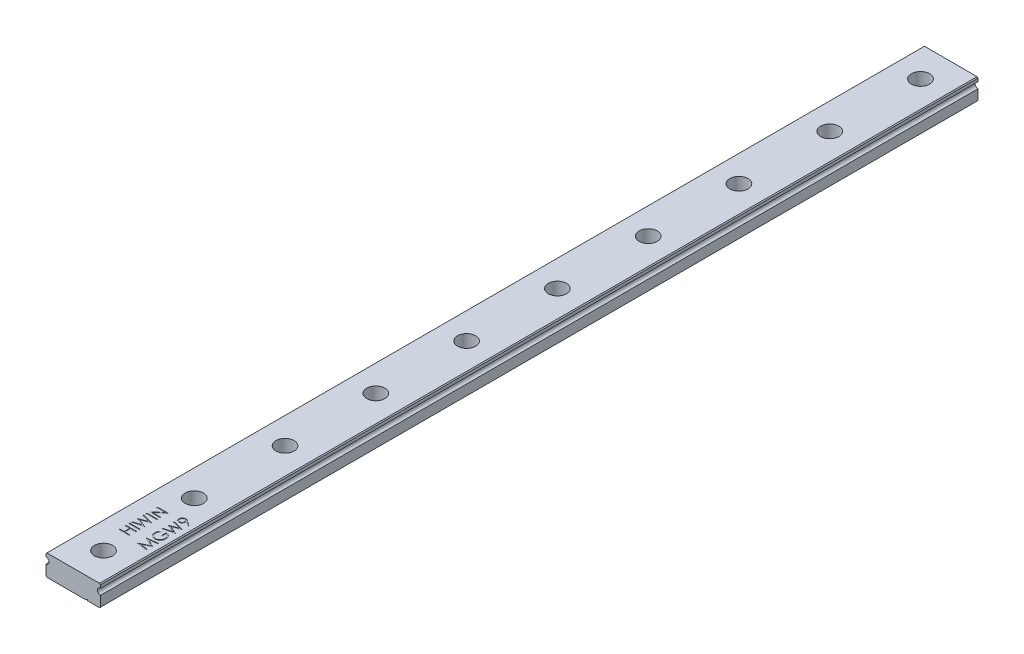
SolidWorks part; units mm, degrees
material "镀铬不锈钢"
ref_plane "前视基准面" through (0, 0, 0) normal (0, 0, 1) x (1, 0, 0)
ref_plane "上视基准面" through (0, 0, 0) normal (0, 1, 0) x (1, 0, 0)
ref_plane "右视基准面" through (0, 0, 0) normal (1, 0, 0) x (0, 0, -1)
sketch "草图1" plane through (0, 0, 0) normal (0, 0, 1) x (1, 0, 0)
  line L12 (9, 5.7) -> (9, 6.7)
  line L13 (0, 7) -> (0, 0) construction
  line L14 (-9, 3.7) -> (-9, 0.3)
  line L15 (-9, 0.3) -> (-8.7, 0)
  line L16 (-9, 6.7) -> (-9, 5.7)
  line L17 (-8.7, 0) -> (4.2, 0)
  line L18 (8.7, 0) -> (9, 0.3)
  line L19 (9, 0.3) -> (9, 3.7)
  line L20 (8.7, 7) -> (-8.7, 7)
  line L21 (9, 6.7) -> (8.7, 7)
  line L22 (4.8, 0) -> (8.7, 0)
  line L23 (-8.7, 7) -> (-9, 6.7)
  arc A3 (-9, 3.7) -> (-9, 5.7) centre (-9, 4.7) ccw
  arc A4 (9, 5.7) -> (9, 3.7) centre (9, 4.7) ccw
  arc A5 (4.8, 0) -> (4.2, 0) centre (4.5, 0) ccw
extrude "凸台-拉伸1" add sketch "草图1" against normal blind 290
hole_wizard "M3 六角凹头螺钉的柱形沉头孔1" positions "草图3" profile "草图2" counterbore size "M3" standard "ISO" end condition through all
sketch "草图3" plane through (-0.0845, 7, -67.9937) normal (0, 1, 0) x (-1, 0, 0)
  line L5 (-8.7845, 67.9937) -> (8.6155, 67.9937) construction
  point P15 (-0.0845, 57.9937)
  dimension "D1" = 10
sketch "草图2" plane through (0, 7, -10) normal (1, 0, 0) x (0, 0, 1)
  line L0 (0, 0) -> (0, 7)
  line L1 (0, 7) -> (1.75, 7)
  line L3 (1.75, 7) -> (1.75, 4.5)
  line L4 (1.75, 4.5) -> (3, 4.5)
  line L5 (3, 4.5) -> (3, 0)
  line L7 (3, 0) -> (0, 0)
  line L11 (0, -6.35) -> (0, 107.95) construction
  dimension "通孔孔直径" = 3.5
  dimension "通孔孔深度" = 7
  dimension "柱形沉头孔直径" = 6
  dimension "柱形沉头孔深度" = 4.5
pattern_linear "阵列(线性)1" count 10 spacing 30 along (0, 0, -1) of "M3 六角凹头螺钉的柱形沉头孔1"
sketch "草图4" plane through (0, 7, 0) normal (0, 1, 0) x (1, 0, 0)
  line L2 (0, 10) -> (0, 40) construction
  text T0 "HIWIN\r\nMGW9"
extrude "切除-拉伸1" cut sketch "草图4" against normal blind 0.1
equation "\"D1@凸台-拉伸1\" = 2 * \"D1@草图3\" + \"D3@阵列(线性)1\" *  (\"D1@阵列(线性)1\" - 1  ) "
